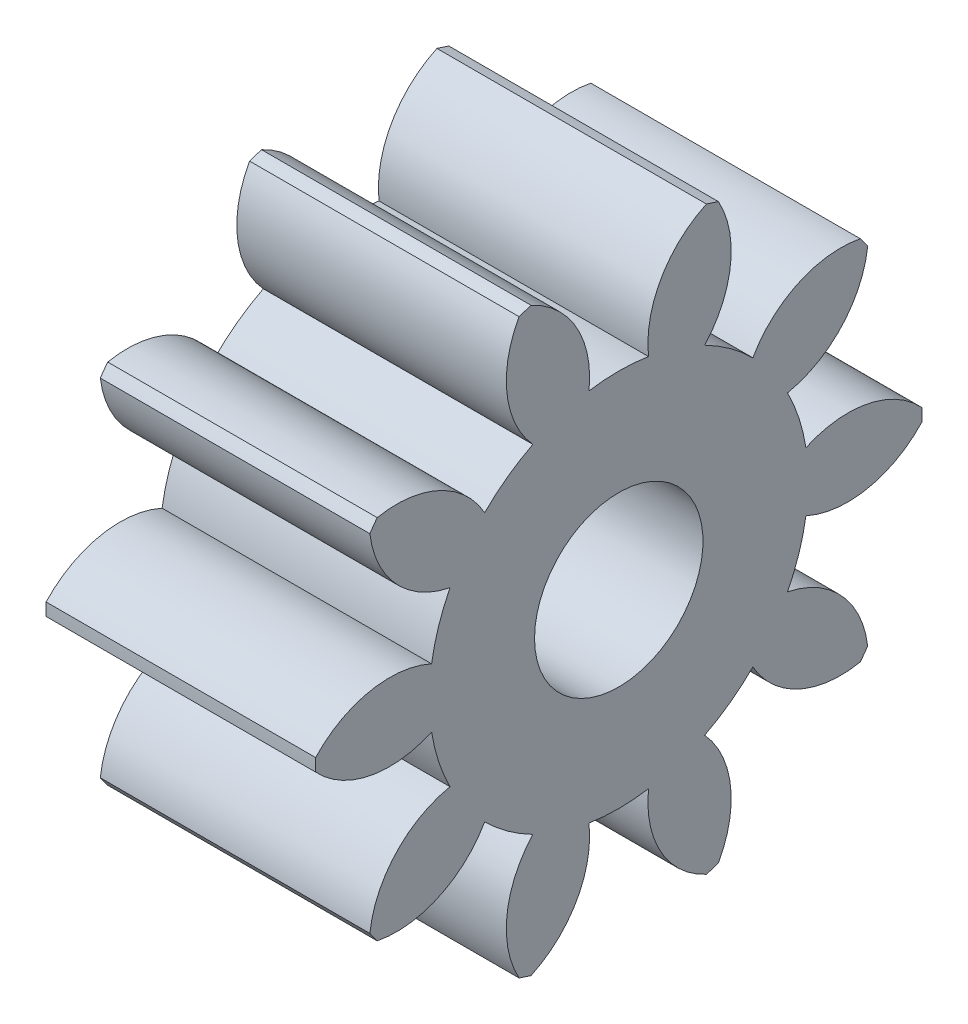
SolidWorks part; units mm, degrees
ref_plane "Plane1" through (0, 0, 0) normal (0, 0, 1) x (1, 0, 0)
ref_plane "Plane2" through (0, 0, 0) normal (0, 1, 0) x (1, 0, 0)
ref_plane "Plane3" through (0, 0, 0) normal (1, 0, 0) x (0, 0, -1)
sketch "HoldingSke" plane through (0, 0, 0) normal (0, 1, 0) x (1, 0, 0)
  line L0 (0, 0) -> (0.6565, -0.1158)
  line L1 (-15, 0) -> (100, 0) construction
  line L2 (0, 0) -> (-2.1039, 2.3779)
  line L3 (0, 0) -> (-11.863, 4.5341)
  line L4 (0, 0) -> (8.5048, 1.4996)
  line L5 (0, 0) -> (-46.8476, -17.4728)
  line L6 (0, 0) -> (-6.6317, -4.4744)
  line L7 (-2.1039, 2.3779) -> (8.6586, 51.2059)
  line L8 (-76.2, 54.61) -> (-75.3, 54.61)
  line L9 (-71.009, 38.7566) -> (-53.1078, 45.2721)
  line L10 (-76.2, 71.12) -> (104.1128, 71.12)
  line L11 (0, 0) -> (-8, 0)
  line L12 (-76.2, 101.6) -> (-76.147, 101.6)
  line L13 (24.9733, 27.94) -> (52.9518, 28.4284)
  line L14 (24.9733, 27.94) -> (24.9743, 27.94)
  line L15 (24.9733, 27.94) -> (100.4006, 29.5858)
  line L16 (-63.627, -1.5) -> (-12.827, -1.5)
  circle A0 centre (0, 0) radius 2.5
  circle A1 centre (0, 0) radius 5.624
  circle A2 centre (0, 0) radius 37.5
  circle A3 centre (0, 0) radius 2.5
  dimension "MHD" = 11.248
  dimension "Hub_dia" = 75
  dimension "Bore" = 5
  dimension "MBD" = 5
  dimension "Num_teeth" = 10
  dimension "Pitch" = 0.6667
  dimension "Overall_len" = 50
  dimension "Show_teeth" = 10
  dimension "Thickness" = 8
  dimension "OAL" = 50.0001
  dimension "T_dim" = 0.9
  dimension "Ap" = 20
  dimension "H" = 19.05
  dimension "Pitch_radius" = 180.3128
  dimension "Width" = 8
  dimension "Backlash" = 0.053
  dimension "Addendum_fac" = 1
  dimension "Dedendum_fac" = 1.25
  dimension "Clearance_fac" = 0.25
  dimension "Dedendum_add" = 0.001
  dimension "Module" = 1.5
sketch "BasProSke" plane through (0, 0, 0) normal (0, 1, 0) x (1, 0, 0)
  line L0 (-10, 0) -> (60, 0) construction
  line L1 (0, 0) -> (0, 9)
  line L2 (0, 0) -> (8, 0)
  line L3 (8, 0) -> (8, 9)
  line L4 (8, 9) -> (0, 9)
  dimension "Thickness" = 8
  dimension "Diameter" = 18
revolve "Base-Revolve" add sketch "BasProSke" angle 360 about L0
sketch "TooCutSke" plane through (0, 0, 0) normal (1, 0, 0) x (0, 0, -1)
  line L1 (0, 0) -> (0, 107) construction
  line L2 (0, 0) -> (-1.2658, 7.3924) construction
  line L3 (0, 0) -> (-4.5869, 14.117) construction
  line L4 (-1.2658, 7.3924) -> (-2.2934, 7.0585) construction
  arc A0 (0.8839, 5.5541) -> (-0.8839, 5.5541) centre (0, 0) ccw
  arc A1 (2.6378, 8.6313) -> (-2.6378, 8.6313) centre (0, 0) ccw
  circle A2 centre (0, 0) radius 7.5 construction
  circle A3 centre (0, 0) radius 7.0477 construction
  arc A4 (-0.8839, 5.5541) -> (-2.6378, 8.6313) centre (-3.8646, 5.8936) ccw
  arc A5 (2.6378, 8.6313) -> (0.8839, 5.5541) centre (3.8646, 5.8936) ccw
  dimension "Root_dia" = 11.248
  dimension "Overcut_dia" = 18.0508
  dimension "Pitch_dia" = 15
  dimension "Base_dia" = 14.0954
  dimension "Flank_rad" = 3
  dimension "Half_ang" = 18
  dimension "Half_CT" = 1.0805
extrude "ToothCut" cut sketch "TooCutSke" along normal through all
fillet "Breaks" [suppressed] radius 0.03
fillet "RootFillets" [suppressed] radius 0.376
pattern_circular "TeethCuts" count 10 every 36 about axis through (-10, 0, 0) along (1, 0, 0) of "ToothCut", "RootFillets", "Breaks"
sketch "HubNeaOneSke" plane through (0, 0, 0) normal (-1, 0, 0) x (0, 0, 1)
  circle A0 centre (0, 0) radius 5.624
  dimension "Diameter" = 11.248
extrude "HubNearOne" [suppressed] add sketch "HubNeaOneSke" along normal blind 42.0001
sketch "HubNeaBotSke" plane through (0, 0, 0) normal (-1, 0, 0) x (0, 0, 1)
  circle A0 centre (0, 0) radius 5.624
  dimension "Diameter" = 11.248
extrude "HubNearBoth" [suppressed] add sketch "HubNeaBotSke" along normal blind 21
ref_plane "FarPln" through (8, 0, 0) normal (1, 0, 0) x (0, 0, -1)
sketch "HubFarSke" plane through (8, 0, 0) normal (1, 0, 0) x (0, 0, -1)
  circle A0 centre (0, 0) radius 5.624
  dimension "Diameter" = 11.248
extrude "HubFar" [suppressed] add sketch "HubFarSke" along normal blind 21
sketch "BorSke" plane through (0, 0, 0) normal (1, 0, 0) x (0, 0, -1)
  circle A0 centre (0, 0) radius 2.5
  dimension "Diameter" = 5
extrude "Bore" cut sketch "BorSke" along normal mid plane 100.0001
sketch "KeySke" plane through (0, 0, 0) normal (1, 0, 0) x (0, 0, -1)
  line L0 (-1, 0) -> (-1, 3.4)
  line L1 (-1, 3.4) -> (1, 3.4)
  line L2 (1, 3.4) -> (1, 0)
  line L3 (0, 0) -> (0, 34) construction
  line L4 (-1, 0) -> (1, 0)
  dimension "Offset" = 3.4
  dimension "Width" = 2
extrude "Keyway" [suppressed] cut sketch "KeySke" along normal mid plane 100.0001
pattern_circular "Keyway2" [suppressed] count 2 every 90 about axis through (-10, 0, 0) along (1, 0, 0)
equation "' \"Module@HoldingSke\" = 6.35"
equation "' \"Num_teeth@HoldingSke\" = 12"
equation "' \"Ap@HoldingSke\" =  20"
equation "' \"Ap@HoldingSke\" = 20"
equation "' \"Width@HoldingSke\" = 0.5 * 25.4"
equation "' \"Hub_dia@HoldingSke\"= 1 * 25.4"
equation "' \"Hub_dia@HoldingSke\" = 1 * 25.4"
equation "' \"Overall_len@HoldingSke\" = 1.0 * 25.4"
equation "' \"Bore@HoldingSke\" = 0.75 * 25.4"
equation "' \"T_dim@HoldingSke\" = 0.1 * 25.4"
equation "' \"Width@KeySke\" = 0.25 * 25.4"
equation "' \"Show_teeth@HoldingSke\" = 13"
equation "' \"Backlash@HoldingSke\" = 0.009 * 25.4"
equation "' \"Addendum_fac@HoldingSke\" = 1.0"
equation "' \"Dedendum_fac@HoldingSke\" = 1.25"
equation "' \"Dedendum_add@HoldingSke\" = 0.00005 * 25.4"
equation "' \"Clearance_fac@HoldingSke\" = 0.25"
equation "\"Pitch@HoldingSke\" = 1 / \"Module@HoldingSke\""
equation "\"Overcut_dia@TooCutSke\" = (\"Num_teeth@HoldingSke\" + 2 * \"Addendum_fac@HoldingSke\") / \"Pitch@HoldingSke\" + 0.002 * 25.4"
equation "\"Pitch_dia@TooCutSke\" = \"Num_teeth@HoldingSke\" / \"Pitch@HoldingSke\""
equation "\"Base_dia@TooCutSke\" = \"Num_teeth@HoldingSke\" / \"Pitch@HoldingSke\" * cos((\"Ap@HoldingSke\"  * 3.14159265 / 180))"
equation "\"Root_dia@TooCutSke\" = (\"Num_teeth@HoldingSke\" + 2) / \"Pitch@HoldingSke\" - 2 * (\"Addendum_fac@HoldingSke\" + \"Dedendum_fac@HoldingSke\") / \"Pitch@HoldingSke\" - \"Dedendum_add@HoldingSke\" * 2"
equation "\"Half_ang@TooCutSke\" = 180 / \"Num_teeth@HoldingSke\""
equation "\"Half_CT@TooCutSke\" = \"Num_teeth@HoldingSke\" / \"Pitch@HoldingSke\" * sin((3.14159265 / 2 / \"Num_teeth@HoldingSke\")) / 2 - 7 * \"Backlash@HoldingSke\" / 4"
equation "\"Flank_rad@TooCutSke\" = \"Num_teeth@HoldingSke\" / \"Pitch@HoldingSke\" / 5"
equation "\"Radius@RootFillets\" = \"Clearance_fac@HoldingSke\" / \"Pitch@HoldingSke\" + \"Dedendum_add@HoldingSke\""
equation "\"Break_rad@Breaks\" = 0.02 / \"Pitch@HoldingSke\""
equation "\"Thickness@HoldingSke\" = \"Width@HoldingSke\""
equation "\"OAL@HoldingSke\" = \"Thickness@HoldingSke\""
equation "\"MHD@HoldingSke\" = (\"Num_teeth@HoldingSke\" + 2) / \"Pitch@HoldingSke\" - 2 * (\"Addendum_fac@HoldingSke\" + \"Dedendum_fac@HoldingSke\")  / \"Pitch@HoldingSke\" - \"Dedendum_add@HoldingSke\" * 2"
equation "\"MBD@HoldingSke\" = (\"Num_teeth@HoldingSke\" + 2) / \"Pitch@HoldingSke\" - 2 * (\"Addendum_fac@HoldingSke\" + \"Dedendum_fac@HoldingSke\")  / \"Pitch@HoldingSke\" - \"Dedendum_add@HoldingSke\" * 2 - 0.002 * 25.4"
equation "\"MHD@HoldingSke\" = ((sgn( \"MHD@HoldingSke\" - \"Hub_dia@HoldingSke\" )-1)*( \"MHD@HoldingSke\" - \"Hub_dia@HoldingSke\" ))/-2+ \"Hub_dia@HoldingSke\""
equation "\"MBD@HoldingSke\" = ((sgn( \"MBD@HoldingSke\" - \"Bore@HoldingSke\" )-1)*( \"MBD@HoldingSke\" - \"Bore@HoldingSke\" ))/-2+ \"Bore@HoldingSke\""
equation "\"OAL@HoldingSke\" = ((sgn( \"OAL@HoldingSke\" - \"Overall_len@HoldingSke\" )+1)*( \"OAL@HoldingSke\" - \"Overall_len@HoldingSke\" ))/2 + \"Overall_len@HoldingSke\" + 0.000002 * 25.4"
equation "\"Num_teeth@TeethCuts\" = int( \"Show_teeth@HoldingSke\" ) + 1"
equation "\"Num_teeth@TeethCuts\" = ((sgn( \"Num_teeth@TeethCuts\" - \"Num_teeth@HoldingSke\" )-1)*( \"Num_teeth@TeethCuts\" - \"Num_teeth@HoldingSke\" ))/-2+ \"Num_teeth@HoldingSke\""
equation "\"Num_teeth@TeethCuts\" = ((sgn( \"Num_teeth@TeethCuts\" - 2.0)+1)*( \"Num_teeth@TeethCuts\" - 2.0))/2 +2.0"
equation "\"Angle@TeethCuts\" = 360.0 / \"Num_teeth@HoldingSke\""
equation "\"Diameter@BasProSke\" = (\"Num_teeth@HoldingSke\" + 2 * \"Addendum_fac@HoldingSke\") / \"Pitch@HoldingSke\""
equation "\"Thickness@BasProSke\"  = \"Thickness@HoldingSke\""
equation "' \"Fillet_rad@BasProSke\" =  \"Thickness@HoldingSke\" * 0.05"
equation "' \"Fillet_rad@BasProSke\" = \"Thickness@HoldingSke\" * 0.05"
equation "\"MHD@HoldingSke\" = ((sgn( \"MHD@HoldingSke\" - \"Root_dia@TooCutSke\" )-1)*( \"MHD@HoldingSke\" - \"Root_dia@TooCutSke\" ))/-2+ \"Root_dia@TooCutSke\""
equation "\"Diameter@HubNeaOneSke\" = \"MHD@HoldingSke\""
equation "\"Length@HubNearOne\" = \"OAL@HoldingSke\" - \"Thickness@BasProSke\""
equation "\"Diameter@HubNeaBotSke\" = \"MHD@HoldingSke\""
equation "\"Length@HubNearBoth\" = ( \"OAL@HoldingSke\" - \"Thickness@BasProSke\" ) / 2.0"
equation "\"Thickness@FarPln\" = \"Thickness@BasProSke\""
equation "\"Diameter@HubFarSke\" = \"MHD@HoldingSke\""
equation "\"Length@HubFar\" = ( \"OAL@HoldingSke\" - \"Thickness@BasProSke\" ) / 2.0"
equation "\"Diameter@BorSke\" = \"MBD@HoldingSke\""
equation "\"D1@Bore\" = \"OAL@HoldingSke\" * 2.0"
equation "\"D1@Keyway\" = \"OAL@HoldingSke\" * 2.0"
equation "\"Offset@KeySke\" = \"T_dim@HoldingSke\" + \"MBD@HoldingSke\" / 2.0"
